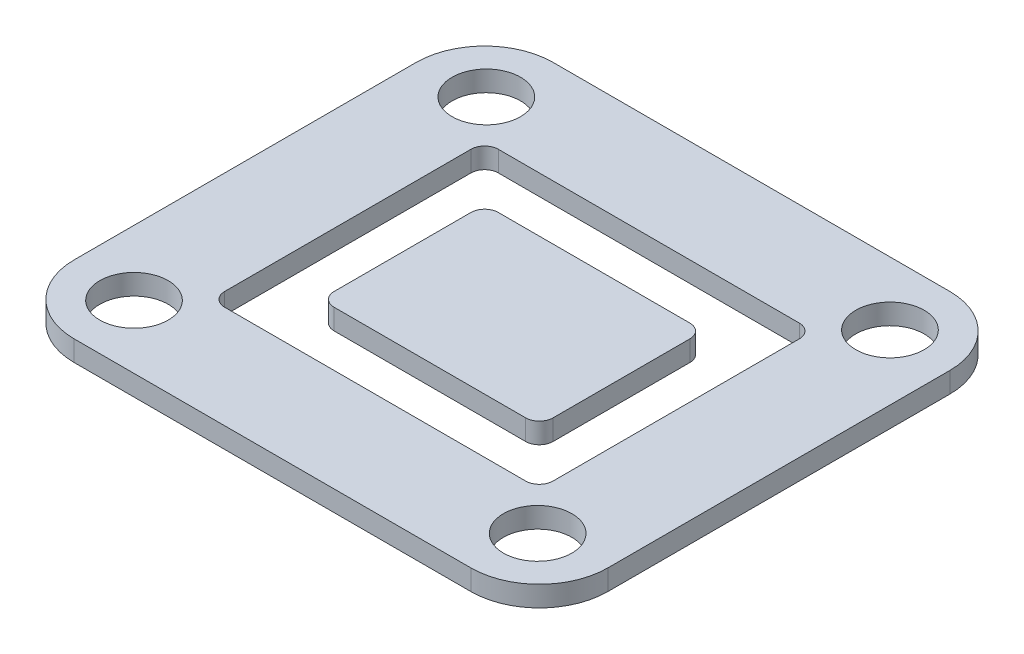
SolidWorks part; units mm, degrees
ref_plane "Front Plane" through (0, 0, 0) normal (0, 0, 1) x (1, 0, 0)
ref_plane "Top Plane" through (0, 0, 0) normal (0, 1, 0) x (1, 0, 0)
ref_plane "Right Plane" through (0, 0, 0) normal (1, 0, 0) x (0, 0, -1)
sketch "Sketch1" plane through (0, 0, 0) normal (0, 1, 0) x (1, 0, 0)
  line L1 (-24.0754, 24.9502) -> (23.9246, 24.9502)
  line L2 (-24.0754, 24.9502) -> (-24.0754, -15.0498)
  line L3 (-24.0754, -15.0498) -> (23.9246, -15.0498)
  line L4 (23.9246, 24.9502) -> (23.9246, -15.0498)
  line L6 (15.9246, 16.9502) -> (-16.0754, 16.9502)
  line L7 (-39.0754, 39.9502) -> (38.9246, 39.9502)
  line L8 (-39.0754, 39.9502) -> (-39.0754, -30.0498)
  line L9 (-39.0754, -30.0498) -> (38.9246, -30.0498)
  line L10 (38.9246, 39.9502) -> (38.9246, -30.0498)
  line L11 (15.9246, 16.9502) -> (15.9246, -7.0498)
  line L12 (15.9246, -7.0498) -> (-16.0754, -7.0498)
  line L17 (-16.0754, 16.9502) -> (-16.0754, -7.0498)
  circle A0 centre (-29.5754, -20.7998) radius 5
  circle A1 centre (-29.5754, 30.7002) radius 5
  circle A2 centre (29.4246, 30.7002) radius 5
  circle A3 centre (29.4246, -20.7998) radius 5
  point P0 (0, 0)
  point P6 (0, 0)
  point P28 (0, 0)
  dimension "D8" = 10
  dimension "D11" = 10
  dimension "D14" = 10
  dimension "D18" = 10
  dimension "D1" = 48
  dimension "D2" = 40
  dimension "D3" = 15
  dimension "D4" = 15
  dimension "D5" = 15
  dimension "D6" = 9.25
  dimension "D7" = 9.5
  dimension "D9" = 9.25
  dimension "D10" = 9.5
  dimension "D12" = 9.5
  dimension "D13" = 9.25
  dimension "D15" = 9.25
  dimension "D16" = 15
  dimension "D17" = 9.5
  dimension "D23" = 70
  dimension "D24" = 78
  dimension "D25" = 8
  dimension "D26" = 8
  dimension "D27" = 8
  dimension "D28" = 8
extrude "Boss-Extrude1" add sketch "Sketch1" along normal blind 3
fillet "Fillet1" radius 2 4 edges at (-24.0754, 1.5, 15.0498) (23.9246, 1.5, 15.0498) (23.9246, 1.5, -24.9502) (-24.0754, 1.5, -24.9502)
fillet "Fillet2" radius 10 4 edges at (-39.0754, 1.5, 30.0498) (-39.0754, 1.5, -39.9502) (38.9246, 1.5, -39.9502) (38.9246, 1.5, 30.0498)
fillet "Fillet3" radius 2 4 edges at (-16.0754, 1.5, 7.0498) (-16.0754, 1.5, -16.9502) (15.9246, 1.5, -16.9502) (15.9246, 1.5, 7.0498)
